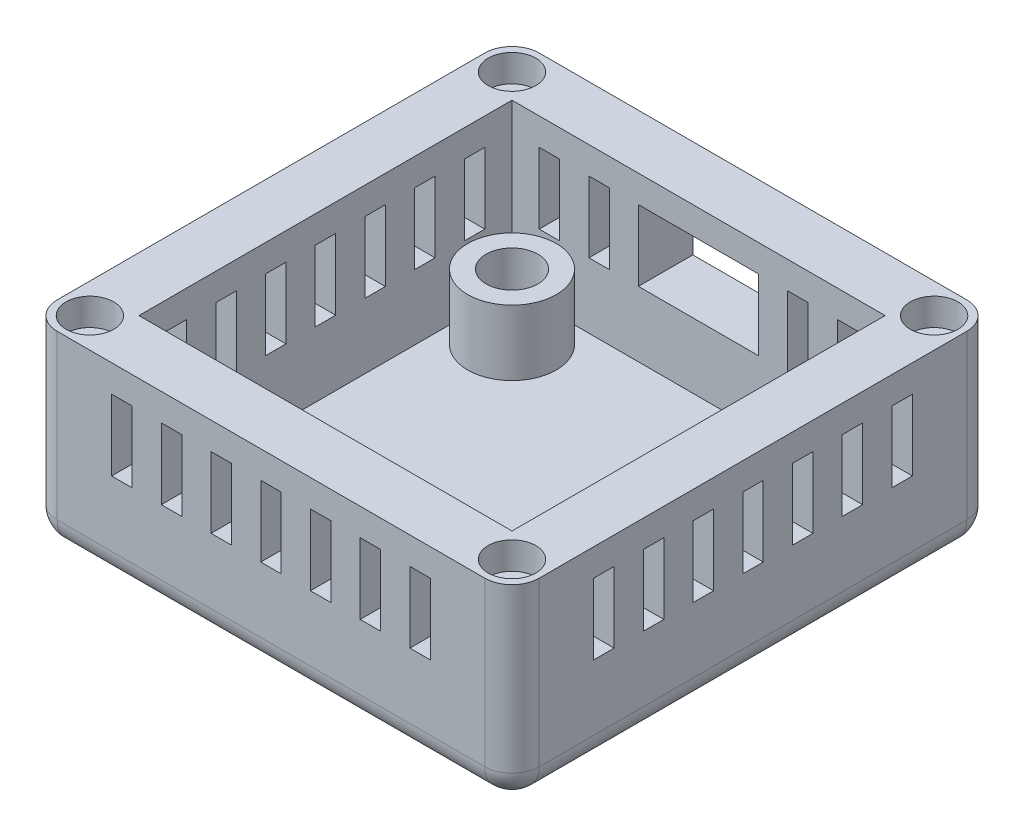
SolidWorks part; units mm, degrees
ref_plane "Plan de face" through (0, 0, 0) normal (0, 0, 1) x (1, 0, 0)
ref_plane "Plan de dessus" through (0, 0, 0) normal (0, 1, 0) x (1, 0, 0)
ref_plane "Plan de droite" through (0, 0, 0) normal (1, 0, 0) x (0, 0, -1)
sketch "Esquisse1" plane through (0, 0, 0) normal (0, 1, 0) x (1, 0, 0)
  line L1 (-17.7, 17.7) -> (17.7, 17.7)
  line L2 (-17.7, 17.7) -> (-17.7, -17.7)
  line L3 (-17.7, -17.7) -> (17.7, -17.7)
  line L4 (17.7, 17.7) -> (17.7, -17.7)
  line L5 (-17.7, 17.7) -> (17.7, -17.7) construction
  line L6 (-17.7, -17.7) -> (17.7, 17.7) construction
  point P0 (0, 0)
  dimension "D1" = 35.4
  dimension "D2" = 35.4
extrude "Boss.-Extru.1" add sketch "Esquisse1" along normal blind 14
sketch "Esquisse2" plane through (0, 14, 0) normal (0, 1, 0) x (1, 0, 0)
  line L1 (-13.7, 13.7) -> (13.7, 13.7)
  line L2 (-13.7, 13.7) -> (-13.7, -13.7)
  line L3 (-13.7, -13.7) -> (13.7, -13.7)
  line L4 (13.7, 13.7) -> (13.7, -13.7)
  line L5 (-13.7, 13.7) -> (13.7, -13.7) construction
  line L6 (-13.7, -13.7) -> (13.7, 13.7) construction
  line L8 (-17.7, 17.7) -> (-17.7, -17.7) construction
  line L9 (17.7, 17.7) -> (-17.7, 17.7) construction
  point P0 (0, 0)
  dimension "D1" = 4
  dimension "D2" = 4
extrude "Enlèv. mat.-Extru.1" cut sketch "Esquisse2" against normal blind 12
sketch "Esquisse3" plane through (0, 2, 0) normal (0, 1, 0) x (1, 0, 0)
  circle A0 centre (0.5643, 0.5937) radius 0.0732
  circle A1 centre (-0.5753, 0.5937) radius 0.0953
  circle A2 centre (-0.617, -0.6521) radius 0.073
  circle A3 centre (0.5643, -0.6274) radius 0.0748
sketch "Esquisse4" plane through (0, 2, 0) normal (0, 1, 0) x (1, 0, 0)
  line L0 (-13.7, 13.7) -> (-13.7, -13.7) construction
  line L1 (-13.7, -13.7) -> (13.7, -13.7) construction
  line L3 (13.7, -13.7) -> (13.7, 13.7) construction
  line L5 (13.7, 13.7) -> (-13.7, 13.7) construction
  circle A0 centre (-10.16, 10.16) radius 1.9
  circle A1 centre (10.16, 10.16) radius 1.9
  circle A2 centre (-10.16, -10.16) radius 1.9
  circle A3 centre (10.16, -10.16) radius 1.9
  circle A4 centre (-10.16, 10.16) radius 3.25
  circle A5 centre (10.16, 10.16) radius 3.25
  circle A6 centre (10.16, -10.16) radius 3.25
  circle A7 centre (-10.16, -10.16) radius 3.25
  dimension "D1" = 6.5
  dimension "D2" = 6.5
  dimension "D3" = 6.5
  dimension "D4" = 6.5
  dimension "D5" = 3.8
  dimension "D6" = 3.8
  dimension "D7" = 3.8
  dimension "D8" = 3.8
  dimension "D9" = 3.54
  dimension "D10" = 3.54
  dimension "D11" = 3.54
  dimension "D12" = 3.54
  dimension "D13" = 3.54
  dimension "D14" = 3.54
  dimension "D15" = 3.54
  dimension "D16" = 3.54
extrude "Boss.-Extru.2" add sketch "Esquisse4" along normal blind 4.8
sketch "Esquisse5" plane through (0, 14, 0) normal (0, 1, 0) x (1, 0, 0)
  line L0 (-17.7, 17.7) -> (-17.7, -17.7) construction
  line L1 (-17.7, -17.7) -> (17.7, -17.7) construction
  line L2 (17.7, 17.7) -> (-17.7, 17.7) construction
  line L3 (17.7, -17.7) -> (17.7, 17.7) construction
  circle A0 centre (15.5, 15.5) radius 1.75
  circle A1 centre (-15.5, 15.5) radius 1.75
  circle A2 centre (-15.5, -15.5) radius 1.75
  circle A3 centre (15.5, -15.5) radius 1.75
  dimension "D9" = 3.5
  dimension "D10" = 3.5
  dimension "D11" = 3.5
  dimension "D12" = 3.5
  dimension "D1" = 2.2
  dimension "D2" = 2.2
  dimension "D3" = 2.2
  dimension "D4" = 2.2
  dimension "D5" = 2.2
  dimension "D6" = 2.2
  dimension "D7" = 2.2
  dimension "D8" = 2.2
extrude "Enlèv. mat.-Extru.2" cut sketch "Esquisse5" against normal blind 2
fillet "Congé6" radius 2 8 edges at (0, 0, -17.7) (17.7, 7, -17.7) (17.7, 0, 0) (17.7, 7, 17.7) (0, 0, 17.7) (-17.7, 7, 17.7) (-17.7, 0, 0) (-17.7, 7, -17.7)
sketch "Esquisse6" plane through (17.7, 0, 0) normal (1, 0, 0) x (0, 0, -1)
  line L0 (-15.7, 14) -> (-15.7, 2) construction
  line L1 (-11.7, 12) -> (-10.2, 12)
  line L2 (-11.7, 12) -> (-11.7, 6.8)
  line L3 (-11.7, 6.8) -> (-10.2, 6.8)
  line L4 (-10.2, 12) -> (-10.2, 6.8)
  line L5 (-11.7, 12) -> (-10.2, 6.8) construction
  line L6 (-11.7, 6.8) -> (-10.2, 12) construction
  line L7 (-15.7, 14) -> (15.7, 14) construction
  line L8 (-15.7, 2) -> (15.7, 2) construction
  line L10 (-8.05, 12) -> (-6.55, 12)
  line L11 (-8.05, 12) -> (-8.05, 6.8)
  line L12 (-8.05, 6.8) -> (-6.55, 6.8)
  line L13 (-6.55, 12) -> (-6.55, 6.8)
  line L14 (-8.05, 12) -> (-6.55, 6.8) construction
  line L15 (-8.05, 6.8) -> (-6.55, 12) construction
  line L16 (-4.4, 12) -> (-2.9, 12)
  line L17 (-4.4, 12) -> (-4.4, 6.8)
  line L18 (-4.4, 6.8) -> (-2.9, 6.8)
  line L19 (-2.9, 12) -> (-2.9, 6.8)
  line L20 (-4.4, 12) -> (-2.9, 6.8) construction
  line L21 (-4.4, 6.8) -> (-2.9, 12) construction
  line L22 (-0.75, 12) -> (0.75, 12)
  line L23 (-0.75, 12) -> (-0.75, 6.8)
  line L24 (-0.75, 6.8) -> (0.75, 6.8)
  line L25 (0.75, 12) -> (0.75, 6.8)
  line L26 (-0.75, 12) -> (0.75, 6.8) construction
  line L27 (-0.75, 6.8) -> (0.75, 12) construction
  line L28 (2.9, 12) -> (4.4, 12)
  line L29 (2.9, 12) -> (2.9, 6.8)
  line L30 (2.9, 6.8) -> (4.4, 6.8)
  line L31 (4.4, 12) -> (4.4, 6.8)
  line L32 (2.9, 12) -> (4.4, 6.8) construction
  line L33 (2.9, 6.8) -> (4.4, 12) construction
  line L34 (6.55, 12) -> (8.05, 12)
  line L35 (6.55, 12) -> (6.55, 6.8)
  line L36 (6.55, 6.8) -> (8.05, 6.8)
  line L37 (8.05, 12) -> (8.05, 6.8)
  line L38 (6.55, 12) -> (8.05, 6.8) construction
  line L39 (6.55, 6.8) -> (8.05, 12) construction
  line L40 (10.2, 12) -> (11.7, 12)
  line L41 (10.2, 12) -> (10.2, 6.8)
  line L42 (10.2, 6.8) -> (11.7, 6.8)
  line L43 (11.7, 12) -> (11.7, 6.8)
  line L44 (10.2, 12) -> (11.7, 6.8) construction
  line L45 (10.2, 6.8) -> (11.7, 12) construction
  line L46 (15.7, 2) -> (15.7, 14) construction
  point P0 (-10.95, 9.4)
  point P12 (-7.3, 9.4)
  point P17 (-3.65, 9.4)
  point P22 (0, 9.4)
  point P27 (3.65, 9.4)
  point P32 (7.3, 9.4)
  point P37 (10.95, 9.4)
  dimension "D1" = 4
  dimension "D2" = 2
  dimension "D3" = 4.8
  dimension "D4" = 1.5
  dimension "D6" = 4
  dimension "D5" = 7
sketch "Esquisse7" plane through (-17.7, 0, 0) normal (-1, 0, 0) x (0, 0, 1)
  line L0 (-15.7, 14) -> (-15.7, 2) construction
  line L1 (-11.7, 6.8) -> (-10.2, 6.8)
  line L2 (-11.7, 6.8) -> (-11.7, 12)
  line L3 (-11.7, 12) -> (-10.2, 12)
  line L4 (-10.2, 6.8) -> (-10.2, 12)
  line L5 (-11.7, 6.8) -> (-10.2, 12) construction
  line L6 (-11.7, 12) -> (-10.2, 6.8) construction
  line L7 (-15.7, 14) -> (15.7, 14) construction
  line L9 (-15.7, 2) -> (15.7, 2) construction
  line L10 (-8.05, 6.8) -> (-6.55, 6.8)
  line L11 (-8.05, 6.8) -> (-8.05, 12)
  line L12 (-8.05, 12) -> (-6.55, 12)
  line L13 (-6.55, 6.8) -> (-6.55, 12)
  line L14 (-8.05, 6.8) -> (-6.55, 12) construction
  line L15 (-8.05, 12) -> (-6.55, 6.8) construction
  line L16 (-4.4, 6.8) -> (-2.9, 6.8)
  line L17 (-4.4, 6.8) -> (-4.4, 12)
  line L18 (-4.4, 12) -> (-2.9, 12)
  line L19 (-2.9, 6.8) -> (-2.9, 12)
  line L20 (-4.4, 6.8) -> (-2.9, 12) construction
  line L21 (-4.4, 12) -> (-2.9, 6.8) construction
  line L22 (-0.75, 6.8) -> (0.75, 6.8)
  line L23 (-0.75, 6.8) -> (-0.75, 12)
  line L24 (-0.75, 12) -> (0.75, 12)
  line L25 (0.75, 6.8) -> (0.75, 12)
  line L26 (-0.75, 6.8) -> (0.75, 12) construction
  line L27 (-0.75, 12) -> (0.75, 6.8) construction
  line L28 (2.9, 6.8) -> (4.4, 6.8)
  line L29 (2.9, 6.8) -> (2.9, 12)
  line L30 (2.9, 12) -> (4.4, 12)
  line L31 (4.4, 6.8) -> (4.4, 12)
  line L32 (2.9, 6.8) -> (4.4, 12) construction
  line L33 (2.9, 12) -> (4.4, 6.8) construction
  line L34 (6.55, 6.8) -> (8.05, 6.8)
  line L35 (6.55, 6.8) -> (6.55, 12)
  line L36 (6.55, 12) -> (8.05, 12)
  line L37 (8.05, 6.8) -> (8.05, 12)
  line L38 (6.55, 6.8) -> (8.05, 12) construction
  line L39 (6.55, 12) -> (8.05, 6.8) construction
  line L40 (10.2, 6.8) -> (11.7, 6.8)
  line L41 (10.2, 6.8) -> (10.2, 12)
  line L42 (10.2, 12) -> (11.7, 12)
  line L43 (11.7, 6.8) -> (11.7, 12)
  line L44 (10.2, 6.8) -> (11.7, 12) construction
  line L45 (10.2, 12) -> (11.7, 6.8) construction
  line L46 (15.7, 2) -> (15.7, 14) construction
  point P0 (-10.95, 9.4)
  point P10 (-7.3, 9.4)
  point P17 (-3.65, 9.4)
  point P22 (0, 9.4)
  point P27 (3.65, 9.4)
  point P32 (7.3, 9.4)
  point P37 (10.95, 9.4)
  dimension "D1" = 4
  dimension "D2" = 2
  dimension "D3" = 1.5
  dimension "D4" = 4.8
  dimension "D6" = 4
  dimension "D5" = 7
sketch "Esquisse8" plane through (0, 0, 17.7) normal (0, 0, 1) x (1, 0, 0)
  line L0 (-15.7, 14) -> (-15.7, 2) construction
  line L1 (-11.7, 6.8) -> (-10.2, 6.8)
  line L2 (-11.7, 6.8) -> (-11.7, 12)
  line L3 (-11.7, 12) -> (-10.2, 12)
  line L4 (-10.2, 6.8) -> (-10.2, 12)
  line L5 (-11.7, 6.8) -> (-10.2, 12) construction
  line L6 (-11.7, 12) -> (-10.2, 6.8) construction
  line L7 (-15.7, 14) -> (15.7, 14) construction
  line L9 (-15.7, 2) -> (15.7, 2) construction
  line L10 (-8.05, 6.8) -> (-6.55, 6.8)
  line L11 (-8.05, 6.8) -> (-8.05, 12)
  line L12 (-8.05, 12) -> (-6.55, 12)
  line L13 (-6.55, 6.8) -> (-6.55, 12)
  line L14 (-8.05, 6.8) -> (-6.55, 12) construction
  line L15 (-8.05, 12) -> (-6.55, 6.8) construction
  line L16 (-4.4, 6.8) -> (-2.9, 6.8)
  line L17 (-4.4, 6.8) -> (-4.4, 12)
  line L18 (-4.4, 12) -> (-2.9, 12)
  line L19 (-2.9, 6.8) -> (-2.9, 12)
  line L20 (-4.4, 6.8) -> (-2.9, 12) construction
  line L21 (-4.4, 12) -> (-2.9, 6.8) construction
  line L22 (-0.75, 6.8) -> (0.75, 6.8)
  line L23 (-0.75, 6.8) -> (-0.75, 12)
  line L24 (-0.75, 12) -> (0.75, 12)
  line L25 (0.75, 6.8) -> (0.75, 12)
  line L26 (-0.75, 6.8) -> (0.75, 12) construction
  line L27 (-0.75, 12) -> (0.75, 6.8) construction
  line L28 (2.9, 6.8) -> (4.4, 6.8)
  line L29 (2.9, 6.8) -> (2.9, 12)
  line L30 (2.9, 12) -> (4.4, 12)
  line L31 (4.4, 6.8) -> (4.4, 12)
  line L32 (2.9, 6.8) -> (4.4, 12) construction
  line L33 (2.9, 12) -> (4.4, 6.8) construction
  line L34 (6.55, 6.8) -> (8.05, 6.8)
  line L35 (6.55, 6.8) -> (6.55, 12)
  line L36 (6.55, 12) -> (8.05, 12)
  line L37 (8.05, 6.8) -> (8.05, 12)
  line L38 (6.55, 6.8) -> (8.05, 12) construction
  line L39 (6.55, 12) -> (8.05, 6.8) construction
  line L40 (10.2, 6.8) -> (11.7, 6.8)
  line L41 (10.2, 6.8) -> (10.2, 12)
  line L42 (10.2, 12) -> (11.7, 12)
  line L43 (11.7, 6.8) -> (11.7, 12)
  line L44 (10.2, 6.8) -> (11.7, 12) construction
  line L45 (10.2, 12) -> (11.7, 6.8) construction
  line L46 (15.7, 2) -> (15.7, 14) construction
  point P0 (-10.95, 9.4)
  point P10 (-7.3, 9.4)
  point P17 (-3.65, 9.4)
  point P22 (0, 9.4)
  point P27 (3.65, 9.4)
  point P32 (7.3, 9.4)
  point P37 (10.95, 9.4)
  dimension "D1" = 4
  dimension "D2" = 2
  dimension "D3" = 1.5
  dimension "D4" = 4.8
  dimension "D6" = 4
  dimension "D5" = 7
sketch "Esquisse9" plane through (0, 0, -17.7) normal (0, 0, -1) x (-1, 0, 0)
  line L0 (-15.7, 14) -> (-15.7, 2) construction
  line L1 (-11.7, 6.8) -> (-10.2, 6.8)
  line L2 (-11.7, 6.8) -> (-11.7, 12)
  line L3 (-11.7, 12) -> (-10.2, 12)
  line L4 (-10.2, 6.8) -> (-10.2, 12)
  line L5 (-11.7, 6.8) -> (-10.2, 12) construction
  line L6 (-11.7, 12) -> (-10.2, 6.8) construction
  line L7 (-15.7, 14) -> (15.7, 14) construction
  line L8 (-8.05, 6.8) -> (-6.55, 6.8)
  line L9 (-15.7, 2) -> (15.7, 2) construction
  line L10 (-8.05, 6.8) -> (-8.05, 12)
  line L11 (-8.05, 12) -> (-6.55, 12)
  line L12 (-6.55, 6.8) -> (-6.55, 12)
  line L13 (-8.05, 6.8) -> (-6.55, 12) construction
  line L14 (-8.05, 12) -> (-6.55, 6.8) construction
  line L15 (-4.4, 6.8) -> (-2.9, 6.8)
  line L16 (-4.4, 6.8) -> (-4.4, 12)
  line L17 (-4.4, 12) -> (-2.9, 12)
  line L18 (-2.9, 6.8) -> (-2.9, 12)
  line L19 (-4.4, 6.8) -> (-2.9, 12) construction
  line L20 (-4.4, 12) -> (-2.9, 6.8) construction
  line L21 (-0.75, 6.8) -> (0.75, 6.8)
  line L22 (-0.75, 6.8) -> (-0.75, 12)
  line L23 (-0.75, 12) -> (0.75, 12)
  line L24 (0.75, 6.8) -> (0.75, 12)
  line L25 (-0.75, 6.8) -> (0.75, 12) construction
  line L26 (-0.75, 12) -> (0.75, 6.8) construction
  line L27 (2.9, 6.8) -> (4.4, 6.8)
  line L28 (2.9, 6.8) -> (2.9, 12)
  line L29 (2.9, 12) -> (4.4, 12)
  line L30 (4.4, 6.8) -> (4.4, 12)
  line L31 (2.9, 6.8) -> (4.4, 12) construction
  line L32 (2.9, 12) -> (4.4, 6.8) construction
  line L33 (6.55, 6.8) -> (8.05, 6.8)
  line L34 (6.55, 6.8) -> (6.55, 12)
  line L35 (6.55, 12) -> (8.05, 12)
  line L36 (8.05, 6.8) -> (8.05, 12)
  line L37 (6.55, 6.8) -> (8.05, 12) construction
  line L38 (6.55, 12) -> (8.05, 6.8) construction
  line L39 (10.2, 6.8) -> (11.7, 6.8)
  line L40 (10.2, 6.8) -> (10.2, 12)
  line L41 (10.2, 12) -> (11.7, 12)
  line L42 (11.7, 6.8) -> (11.7, 12)
  line L43 (10.2, 6.8) -> (11.7, 12) construction
  line L44 (10.2, 12) -> (11.7, 6.8) construction
  line L45 (15.7, 2) -> (15.7, 14) construction
  point P0 (-10.95, 9.4)
  point P13 (-7.3, 9.4)
  point P18 (-3.65, 9.4)
  point P23 (0, 9.4)
  point P28 (3.65, 9.4)
  point P33 (7.3, 9.4)
  point P38 (10.95, 9.4)
  dimension "D1" = 4
  dimension "D2" = 2
  dimension "D3" = 1.5
  dimension "D4" = 4.8
  dimension "D6" = 4
  dimension "D5" = 7
extrude "Enlèv. mat.-Extru.9" cut sketch "Esquisse9" against normal blind 4
extrude "Enlèv. mat.-Extru.10" cut sketch "Esquisse8" against normal blind 4
extrude "Enlèv. mat.-Extru.11" cut sketch "Esquisse7" against normal blind 4
extrude "Enlèv. mat.-Extru.12" cut sketch "Esquisse6" against normal blind 4
sketch "Esquisse10" plane through (0, 0, -17.7) normal (0, 0, -1) x (-1, 0, 0)
  line L1 (-4.4, 12) -> (4.4193, 12)
  line L2 (-4.4, 12) -> (-4.4, 6.8)
  line L3 (-4.4, 6.8) -> (4.4193, 6.8)
  line L4 (4.4193, 12) -> (4.4193, 6.8)
  dimension "D1" = 8.8193
  dimension "D2" = 5.2
extrude "Enlèv. mat.-Extru.13" cut sketch "Esquisse10" against normal blind 6
